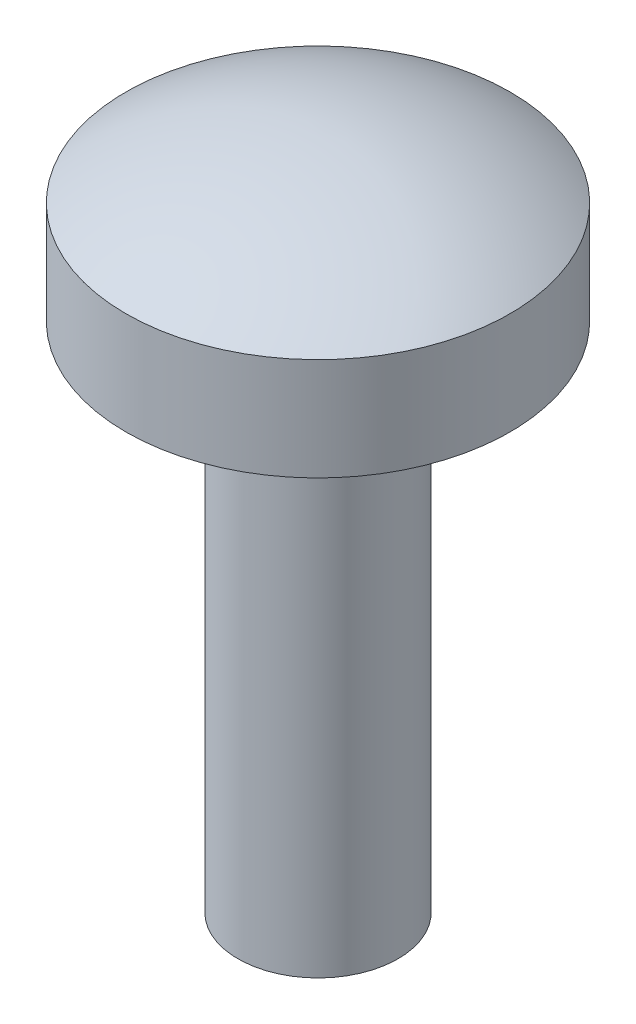
SolidWorks part; units mm, degrees
ref_plane "Front Plane" through (0, 0, 0) normal (0, 0, 1) x (1, 0, 0)
ref_plane "Top Plane" through (0, 0, 0) normal (0, 1, 0) x (1, 0, 0)
ref_plane "Right Plane" through (0, 0, 0) normal (1, 0, 0) x (0, 0, -1)
sketch "Sketch2" plane through (0, 0, 0) normal (1, 0, 0) x (0, 0, -1)
  line L0 (0, 0) -> (3, 0)
  line L1 (55, 0) -> (-55, 0) construction
  line L2 (3, 0) -> (3, 1.6)
  line L3 (0, 55) -> (0, -55) construction
  line L4 (0, 2.52) -> (0, 0)
  arc A0 (3, 1.6) -> (0, 2.52) centre (0, -2.8313) ccw
  dimension "D4" = 0
  dimension "D1" = 3
  dimension "D2" = 2.52
  dimension "D3" = 1.6
revolve "Revolve1" add sketch "Sketch2" angle 360 about L4
sketch "Sketch3" plane through (0, 0, 0) normal (0, -1, 0) x (1, 0, 0)
  circle A0 centre (0, 0) radius 1.25
  dimension "D1" = 2.5
extrude "Boss-Extrude1" add sketch "Sketch3" along normal blind 8
